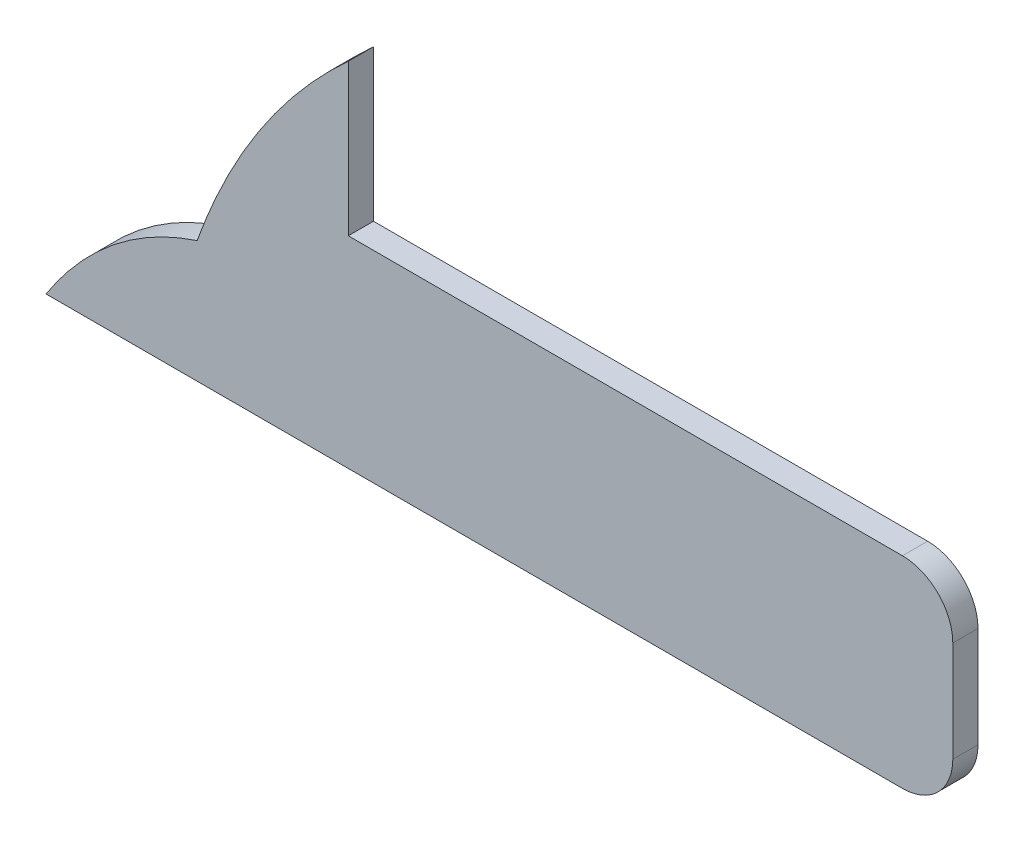
SolidWorks part; units mm, degrees
ref_plane "Front Plane" through (0, 0, 0) normal (0, 0, 1) x (1, 0, 0)
ref_plane "Top Plane" through (0, 0, 0) normal (0, 1, 0) x (1, 0, 0)
ref_plane "Right Plane" through (0, 0, 0) normal (1, 0, 0) x (0, 0, -1)
sketch "Sketch2" plane through (0, 0, 0) normal (0, 0, 1) x (1, 0, 0)
  line L0 (0, 0) -> (431.8, 0)
  line L1 (76.2, 0) -> (76.2, 142.4009) construction
  line L2 (152.4, 0) -> (152.4, 149.6555) construction
  line L3 (457.2, 25.4) -> (457.2, 76.2)
  line L6 (431.8, 101.6) -> (152.4, 101.6)
  line L7 (152.4, 101.6) -> (152.4, 177.8)
  arc A0 (431.8, 0) -> (457.2, 25.4) centre (431.8, 25.4) ccw
  arc A1 (457.2, 76.2) -> (431.8, 101.6) centre (431.8, 76.2) ccw
  spline S0 degree 2 poles (0, 0) (29.783, 46.1278) (76.2, 61.4013) knots 0 0 0 0.939646 0.939646 0.939646
  spline S1 degree 2 poles (76.2, 61.4013) (101.2474, 131.1992) (152.4, 177.8) knots 0 0 0 0.857767 0.857767 0.857767
  point P12 (457.2, 0)
  point P16 (76.2, 61.4013)
  dimension "D6" = 101.6
  dimension "D7" = 140.5405
  dimension "D5" = 25.4
  dimension "D1" = 457.2
  dimension "D2" = 76.2
  dimension "D3" = 152.4
  dimension "D4" = 76.2
extrude "Boss-Extrude1" add sketch "Sketch2" along normal blind 12.7
